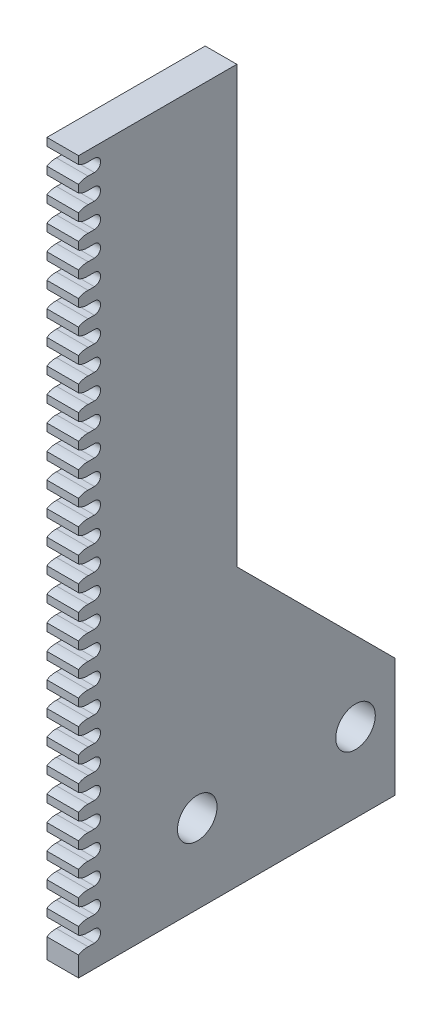
SolidWorks part; units mm, degrees
ref_plane "Спереди" through (0, 0, 0) normal (0, 0, 1) x (1, 0, 0)
ref_plane "Сверху" through (0, 0, 0) normal (0, 1, 0) x (1, 0, 0)
ref_plane "Справа" through (0, 0, 0) normal (1, 0, 0) x (0, 0, -1)
sketch "Эскиз1" plane through (0, 0, 0) normal (1, 0, 0) x (0, 0, -1)
  line L0 (40, 15) -> (20, 35)
  line L1 (0, 0) -> (40, 0)
  line L2 (0, 0) -> (0, 90)
  line L3 (0, 90) -> (20, 90)
  line L4 (40, 0) -> (40, 15)
  line L5 (20, 35) -> (20, 90)
  line L6 (0, 10) -> (40, 10) construction
  circle A0 centre (15, 10) radius 2.5
  circle A1 centre (35, 10) radius 2.5
  dimension "D7" = 5
  dimension "D1" = 40
  dimension "D2" = 90
  dimension "D3" = 20
  dimension "D4" = 15
  dimension "D5" = 20
  dimension "D6" = 10
  dimension "D8" = 20
  dimension "D9" = 5
extrude "Бобышка-Вытянуть1" add sketch "Эскиз1" along normal blind 4
sketch "Эскиз2" plane through (4, 0, 0) normal (1, 0, 0) x (0, 0, -1)
  line L0 (4, 90) -> (4, 0) construction
  line L1 (20, 90) -> (0, 90) construction
  line L2 (0, 0) -> (40, 0) construction
  line L3 (0, 90) -> (0, 0) construction
  line L4 (2, 90) -> (2, 4.3773) construction
  line L5 (4, 3.5963) -> (0, 3.5963) construction
  line L6 (0, 4.6781) -> (0, 2.5145)
  line L9 (1.2071, 2.8154) -> (2, 2.8154)
  line L11 (1.2071, 4.3773) -> (2, 4.3773)
  line L12 (2, 2.8154) -> (2, 0) construction
  arc A0 (2, 2.8154) -> (2, 4.3773) centre (2, 3.5963) ccw
  spline S0 degree 2 poles (1.2071, 2.8154) (0.5506, 2.8422) (0, 2.5145) knots 0 0 0 1 1 1
  spline S1 degree 2 poles (1.2071, 4.3773) (0.5506, 4.3505) (0, 4.6781) knots 0 0 0 1 1 1
  dimension "D1" = 4
  dimension "D2" = 2
  dimension "D3" = 1.5619
extrude "Вырез-Вытянуть1" cut sketch "Эскиз2" against normal blind 4
pattern_linear "Линейный массив1" count 28 spacing 3.1237 along (0, -1, 0) of "Вырез-Вытянуть1"
